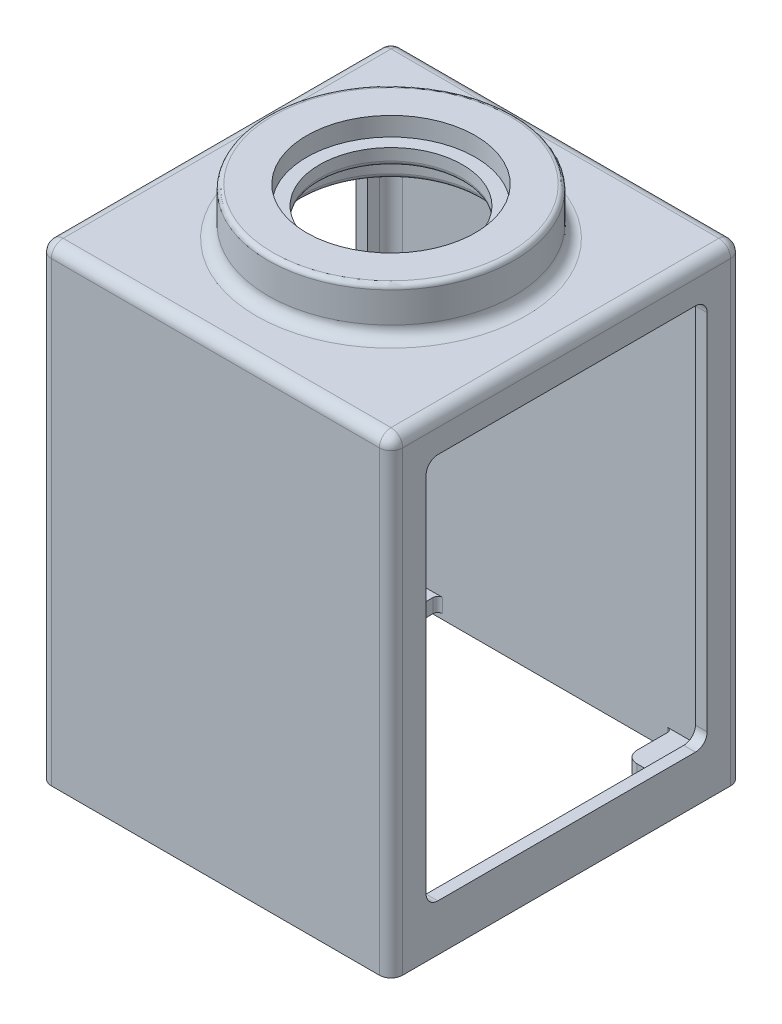
SolidWorks part; units mm, degrees
ref_plane "Front Plane" through (0, 0, 0) normal (0, 0, 1) x (1, 0, 0)
ref_plane "Top Plane" through (0, 0, 0) normal (0, 1, 0) x (1, 0, 0)
ref_plane "Right Plane" through (0, 0, 0) normal (1, 0, 0) x (0, 0, -1)
sketch "Sketch1" plane through (0, 0, 0) normal (0, 1, 0) x (1, 0, 0)
  circle A4 centre (0, 0) radius 66.675
  dimension "D1" = 133.35
extrude "Boss-Extrude1" add sketch "Sketch1" along normal blind 25.4
sketch "Sketch3" plane through (0, 25.4, 0) normal (0, 1, 0) x (1, 0, 0)
  circle A0 centre (0, 0) radius 45.72
  dimension "D1" = 91.44
extrude "Cut-Extrude3" cut sketch "Sketch3" against normal blind 10.16
fillet "Fillet1" radius 2.54 1 edges at (0, 25.4, 66.675)
sketch "Sketch4" plane through (0, 0, 0) normal (0, -1, 0) x (1, 0, 0)
  line L1 (88.9, 95.25) -> (-88.9, 95.25)
  line L2 (95.25, 88.9) -> (95.25, -88.9)
  line L3 (88.9, -95.25) -> (-88.9, -95.25)
  line L4 (-95.25, 88.9) -> (-95.25, -88.9)
  line L5 (95.25, 95.25) -> (-95.25, -95.25) construction
  line L6 (95.25, -95.25) -> (-95.25, 95.25) construction
  arc A0 (-88.9, -95.25) -> (-95.25, -88.9) centre (-88.9, -88.9) cw
  arc A1 (-88.9, 95.25) -> (-95.25, 88.9) centre (-88.9, 88.9) ccw
  arc A2 (88.9, 95.25) -> (95.25, 88.9) centre (88.9, 88.9) cw
  arc A3 (95.25, -88.9) -> (88.9, -95.25) centre (88.9, -88.9) cw
  point P0 (0, 0)
  dimension "D3" = 6.35
  dimension "D1" = 190.5
  dimension "D2" = 190.5
extrude "Boss-Extrude2" add sketch "Sketch4" along normal blind 254
fillet "Fillet2" radius 6.35 8 edges at (93.3901, 0, 93.3901) (95.25, 0, 0) (93.3901, 0, -93.3901) (0, 0, -95.25) (-93.3901, 0, -93.3901) (-95.25, 0, 0) (-93.3901, 0, 93.3901) (0, 0, 95.25)
sketch "Sketch5" plane through (0, -254, 0) normal (0, -1, 0) x (1, 0, 0)
  line L27 (88.9, -88.9) -> (88.9, 88.9)
  line L28 (-88.9, -88.9) -> (88.9, -88.9)
  line L29 (-88.9, 88.9) -> (-88.9, -88.9)
  line L30 (88.9, 88.9) -> (-88.9, 88.9)
  line L31 (88.9, -82.55) -> (88.9, 82.55)
  line L32 (-82.55, -88.9) -> (82.55, -88.9)
  line L33 (-88.9, 82.55) -> (-88.9, -82.55)
  line L34 (82.55, 88.9) -> (-82.55, 88.9)
  arc A15 (88.9, -82.55) -> (82.55, -88.9) centre (82.55, -82.55) cw
  arc A16 (-82.55, -88.9) -> (-88.9, -82.55) centre (-82.55, -82.55) cw
  arc A17 (88.9, 82.55) -> (82.55, 88.9) centre (82.55, 82.55) ccw
  arc A18 (-88.9, 82.55) -> (-82.55, 88.9) centre (-82.55, 82.55) cw
  dimension "D2" = 6.35
  dimension "D1" = 6.35
extrude "Cut-Extrude4" cut sketch "Sketch5" against normal blind 247.65
sketch "Sketch7" plane through (0, 15.24, 0) normal (0, 1, 0) x (1, 0, 0)
  circle A0 centre (0, 0) radius 38.735
  dimension "D1" = 77.47
extrude "Cut-Extrude5" cut sketch "Sketch7" against normal up to surface (21.59 mm away) up to face at (0, -6.35, 0)
fillet "Fillet3" radius 6.35 1 edges at (0, 0, 66.675)
sketch "Sketch8" plane through (-95.25, 0, 0) normal (-1, 0, 0) x (0, 0, 1)
  line L0 (0, 0) -> (0, -254) construction
  line L1 (88.9, -254) -> (-88.9, -254) construction
  line L2 (88.9, -6.35) -> (-88.9, -6.35) construction
  line L3 (-69.85, -228.6) -> (69.85, -228.6)
  line L4 (-76.2, -222.25) -> (-76.2, -25.4)
  line L5 (-69.85, -19.05) -> (69.85, -19.05)
  line L6 (76.2, -222.25) -> (76.2, -25.4)
  line L7 (-76.2, -228.6) -> (76.2, -19.05) construction
  line L8 (-76.2, -19.05) -> (76.2, -228.6) construction
  line L9 (-88.9, -254) -> (-88.9, -6.35) construction
  arc A0 (-69.85, -228.6) -> (-76.2, -222.25) centre (-69.85, -222.25) cw
  arc A1 (69.85, -228.6) -> (76.2, -222.25) centre (69.85, -222.25) ccw
  arc A2 (69.85, -19.05) -> (76.2, -25.4) centre (69.85, -25.4) cw
  arc A3 (-76.2, -25.4) -> (-69.85, -19.05) centre (-69.85, -25.4) cw
  point P5 (0, -123.825)
  dimension "D4" = 6.35
  dimension "D1" = 12.7
  dimension "D2" = 12.7
  dimension "D3" = 25.4
extrude "Cut-Extrude6" cut sketch "Sketch8" against normal up to surface (190.5 mm away) up to face at (95.25, -130.175, 0)
sketch "Sketch9" plane through (0, -6.35, 0) normal (0, -1, 0) x (1, 0, 0)
  circle A0 centre (0, 0) radius 48.26
  dimension "D1" = 96.52
extrude "Cut-Extrude7" cut sketch "Sketch9" against normal blind 12.7
fillet "Fillet4" radius 2.54 3 edges at (0, -6.35, -48.26) (0, 6.35, -48.26) (0, 6.35, -38.735)
ref_plane "Plane1" through (0, -251.206, 0) normal (0, -1, 0) x (-1, 0, 0)
sketch "Sketch10" plane through (0, -251.206, 0) normal (0, -1, 0) x (-1, 0, 0)
  line L0 (0, 88.9) -> (0, -88.9) construction
  line L1 (82.55, 88.9) -> (-82.55, 88.9) construction
  line L2 (-82.55, -88.9) -> (82.55, -88.9) construction
  line L3 (88.9, 0) -> (-88.9, 0) construction
  line L4 (88.9, -82.55) -> (88.9, 82.55) construction
  line L5 (-88.9, 82.55) -> (-88.9, -82.55) construction
  line L6 (88.9, -82.55) -> (88.9, 82.55) construction
  line L7 (88.9, 63.5) -> (69.85, 63.5)
  line L8 (88.9, 63.5) -> (88.9, 88.9)
  line L9 (88.9, 88.9) -> (63.5, 88.9)
  line L10 (63.5, 69.85) -> (63.5, 88.9)
  line L11 (82.55, 88.9) -> (-82.55, 88.9) construction
  line L12 (88.9, -88.9) -> (63.5, -88.9)
  line L13 (63.5, -69.85) -> (63.5, -88.9)
  line L14 (88.9, -63.5) -> (69.85, -63.5)
  line L15 (88.9, -63.5) -> (88.9, -88.9)
  line L16 (-88.9, -63.5) -> (-88.9, -88.9)
  line L17 (-88.9, -63.5) -> (-69.85, -63.5)
  line L18 (-63.5, -69.85) -> (-63.5, -88.9)
  line L19 (-88.9, -88.9) -> (-63.5, -88.9)
  line L20 (-88.9, 88.9) -> (-63.5, 88.9)
  line L21 (-63.5, 69.85) -> (-63.5, 88.9)
  line L22 (-88.9, 63.5) -> (-69.85, 63.5)
  line L23 (-88.9, 63.5) -> (-88.9, 88.9)
  arc A0 (69.85, 63.5) -> (63.5, 69.85) centre (69.85, 69.85) cw
  arc A1 (69.85, -63.5) -> (63.5, -69.85) centre (69.85, -69.85) ccw
  arc A2 (-69.85, -63.5) -> (-63.5, -69.85) centre (-69.85, -69.85) cw
  arc A3 (-69.85, 63.5) -> (-63.5, 69.85) centre (-69.85, 69.85) ccw
  point P22 (63.5, 63.5)
  dimension "D3" = 6.35
  dimension "D1" = 25.4
  dimension "D2" = 25.4
extrude "Boss-Extrude3" add sketch "Sketch10" against normal blind 7.62
fillet "Fillet5" radius 2.54 8 edges at (88.9, -247.396, 63.5) (63.5, -247.396, 88.9) (-63.5, -247.396, 88.9) (-88.9, -247.396, 63.5) (-63.5, -247.396, -88.9) (-88.9, -247.396, -63.5) (88.9, -247.396, -63.5) (63.5, -247.396, -88.9)
sketch "Sketch11" plane through (0, -251.206, 0) normal (0, -1, 0) x (-1, 0, 0)
  line L0 (88.9, 0) -> (-88.9, 0) construction
  line L1 (88.9, -82.55) -> (88.9, 82.55) construction
  line L2 (-88.9, 82.55) -> (-88.9, -82.55) construction
  line L3 (0, 88.9) -> (0, -88.9) construction
  line L4 (82.55, 88.9) -> (-82.55, 88.9) construction
  line L5 (-82.55, -88.9) -> (82.55, -88.9) construction
  line L6 (63.5, 76.2) -> (88.9, 76.2) construction
  line L7 (63.5, 86.36) -> (63.5, 69.85) construction
  line L8 (88.9, -82.55) -> (88.9, 82.55) construction
  line L9 (82.55, 88.9) -> (60.96, 88.9) construction
  line L11 (76.2, 88.9) -> (76.2, 63.5) construction
  line L12 (69.85, 63.5) -> (86.36, 63.5) construction
  circle A0 centre (76.2, 76.2) radius 2.2352
  circle A1 centre (76.2, -76.2) radius 2.2352
  circle A2 centre (-76.2, -76.2) radius 2.2352
  circle A3 centre (-76.2, 76.2) radius 2.2352
  point P25 (76.2, 76.2)
  dimension "D2" = 4.4704
  dimension "D1" = 12.7
extrude "Cut-Extrude8" cut sketch "Sketch11" against normal blind 6.7564
